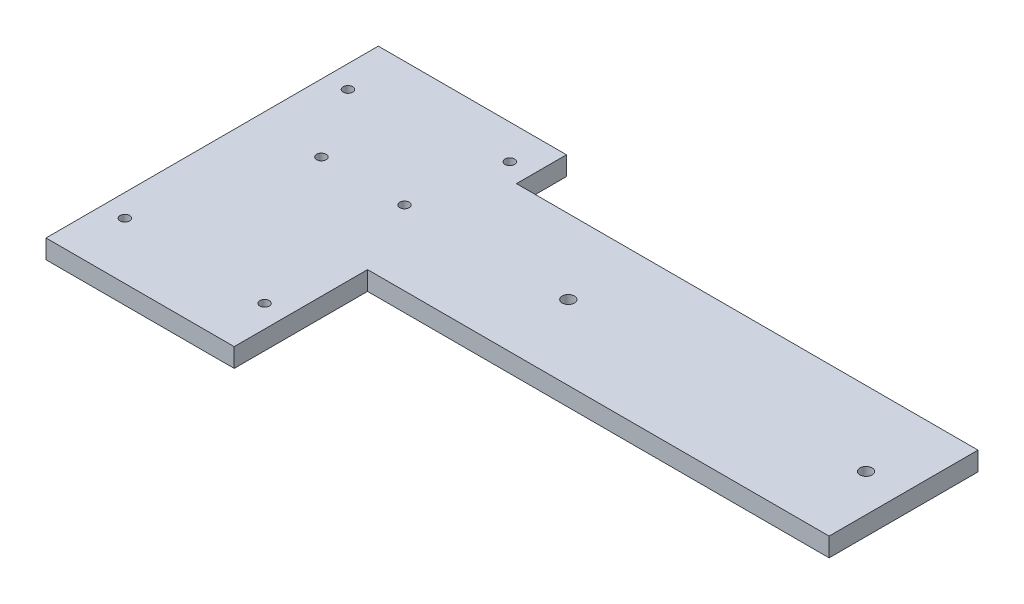
SolidWorks part; units mm, degrees
ref_plane "Front Plane" through (0, 0, 0) normal (0, 0, 1) x (1, 0, 0)
ref_plane "Top Plane" through (0, 0, 0) normal (0, 1, 0) x (1, 0, 0)
ref_plane "Right Plane" through (0, 0, 0) normal (1, 0, 0) x (0, 0, -1)
sketch "Sketch1" plane through (0, 0, 0) normal (0, 1, 0) x (1, 0, 0)
  line L0 (-50.7, 14) -> (-2.5, 14) construction
  line L1 (-2.5, 14) -> (-2.5, 12.7) construction
  line L2 (-50.7, 88.9) -> (-50.7, 14) construction
  line L3 (-2.5, 95.05) -> (-2.5, 12.7) construction
  line L4 (-35.5, 64.8) -> (-7.6, 64.8) construction
  line L5 (-53.2, 101.6) -> (0, 101.6)
  line L6 (-53.2, 101.6) -> (-53.2, 0)
  line L7 (-53.2, 0) -> (0, 0)
  line L8 (0, 101.6) -> (0, 0)
  line L9 (-58.2, 106.6) -> (-58.2, -5)
  line L10 (-58.2, -5) -> (5, -5)
  line L11 (5, 106.6) -> (5, -5)
  line L12 (-58.2, 106.6) -> (5, 106.6)
  circle A0 centre (-50.7, 88.9) radius 1.6
  circle A1 centre (-2.5, 95.05) radius 1.6
  circle A2 centre (-35.5, 64.8) radius 1.6
  circle A3 centre (-7.6, 64.8) radius 1.6
  circle A4 centre (-50.7, 14) radius 1.6
  circle A5 centre (-2.5, 12.7) radius 1.6
  dimension "D1" = 3.2
  dimension "D13" = 5
  dimension "D2" = 48.2
  dimension "D3" = 1.3
  dimension "D4" = 82.35
  dimension "D5" = 74.9
  dimension "D6" = 50.8
  dimension "D7" = 15.2
  dimension "D8" = 27.9
  dimension "D9" = 14
  dimension "D10" = 101.6
  dimension "D11" = 2.5
  dimension "D12" = 2.5
extrude "Boss-Extrude1" add sketch "Sketch1" along normal blind 6.35 contours L12 L9 L10 L11 L5 L8 L7 L6 | L8 L5 L6 L7 A5 A4 A3 A2 A1 A0
sketch "Sketch2" plane through (0, 6.35, 0) normal (0, 1, 0) x (1, 0, 0)
  line L0 (5, 106.6) -> (5, -5) construction
  line L1 (5, 89.8) -> (160, 89.8)
  line L2 (5, 89.8) -> (5, 39.8)
  line L3 (5, 39.8) -> (160, 39.8)
  line L4 (160, 89.8) -> (160, 39.8)
  line L5 (-7.6, 64.8) -> (160, 64.8) construction
  circle A0 centre (47.4, 64.8) radius 2.05
  circle A1 centre (147.4, 64.8) radius 2.05
  point P13 (42.2299, 64.8)
  point P14 (166.9931, 64.8)
  point P15 (160, 64.8)
  dimension "D3" = 4.1
  dimension "D4" = 4.1
  dimension "D1" = 155
  dimension "D2" = 50
  dimension "D5" = 55
  dimension "D6" = 100
extrude "Boss-Extrude2" add sketch "Sketch2" against normal up to surface (6.35 mm away) up to face at (-26.6, 0, -50.8)
